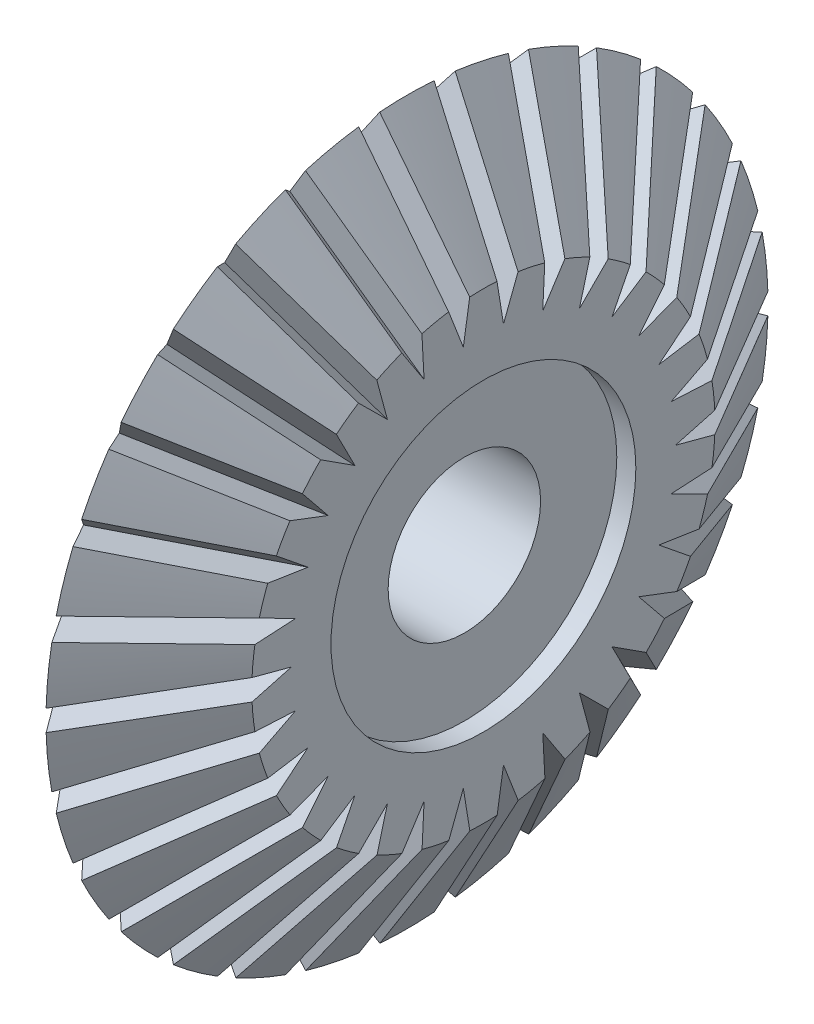
SolidWorks part; units mm, degrees
ref_plane "Alzado" through (0, 0, 0) normal (0, 0, 1) x (1, 0, 0)
ref_plane "Planta" through (0, 0, 0) normal (0, 1, 0) x (1, 0, 0)
ref_plane "Vista lateral" through (0, 0, 0) normal (1, 0, 0) x (0, 0, -1)
sketch "Croquis1" plane through (0, 0, 0) normal (0, 1, 0) x (1, 0, 0)
  line L0 (0, 0) -> (50.7442, 0) construction
  line L1 (0, 0) -> (-50.7442, 0) construction
  line L2 (0, 0) -> (0, 60.7703)
  line L4 (-40.1043, 60.7703) -> (-40.1043, 0)
  line L5 (-40.1043, 0) -> (0, 0)
  line L6 (-40.1043, 60.7703) -> (-20.0522, 94.7362)
  line L7 (-20.0522, 94.7362) -> (0, 60.7703)
revolve "Revolución1" add sketch "Croquis1" angle 360 about L0
ref_plane "Plano1" through (-56.3435, 0, -33.2631) normal (-0.8611, 0, -0.5084) x (-0.5084, 0, 0.8611)
sketch "Croquis2" plane through (-56.3435, 0, -33.2631) normal (-0.8611, 0, -0.5084) x (-0.5084, 0, 0.8611)
  line L0 (-71.3864, 0) -> (-59.3309, 0) construction
  line L1 (-71.3518, -2.7591) -> (-65.3586, 0)
  line L2 (-65.3586, 0) -> (-71.3507, 2.8008)
  line L3 (-71.3507, 2.8008) -> (-75.0368, 0)
  line L4 (-75.0368, 0) -> (-71.3518, -2.7591)
  ellipse E1 centre (10.1941, 0) end of major axis (10.1941, -94.7362) minor radius 81.5805 construction
ref_plane "Plano2" through (26.6042, 0, -15.7061) normal (0.8611, 0, -0.5084) x (-0.5084, 0, -0.8611)
sketch "Croquis3" plane through (26.6042, 0, -15.7061) normal (0.8611, 0, -0.5084) x (-0.5084, 0, -0.8611)
  line L0 (91.7746, 0) -> (0, 0)
sweep "Cortar-Barrer1" cut profiles "Croquis2" path "Croquis3"
pattern_circular "MatrizC2" count 30 over 360 about axis through (0, 0, 0) along (1, 0, 0) of "Cortar-Barrer1"
sketch "Croquis4" plane through (0, 0, 0) normal (1, 0, 0) x (0, 0, -1)
  circle A0 centre (0, 0) radius 40
extrude "Cortar-Extruir1" cut sketch "Croquis4" against normal blind 5
sketch "Croquis5" plane through (-40.1043, 0, 0) normal (-1, 0, 0) x (0, 0, 1)
  circle A0 centre (0, 0) radius 30.1644
extrude "Saliente-Extruir1" add sketch "Croquis5" along normal blind 5
sketch "Croquis6" plane through (-45.1043, 0, 0) normal (-1, 0, 0) x (0, 0, 1)
  circle A0 centre (0, 0) radius 20
extrude "Cortar-Extruir2" cut sketch "Croquis6" against normal blind 135
